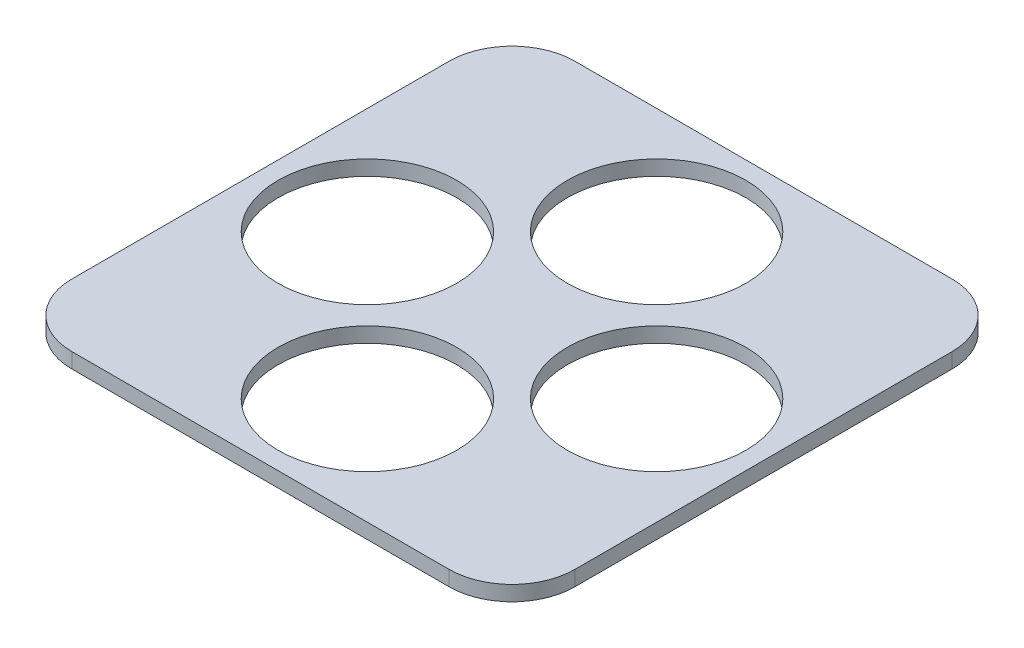
SolidWorks part; units mm, degrees
ref_plane "Plano frontal" through (0, 0, 0) normal (0, 0, 1) x (1, 0, 0)
ref_plane "Plano superior" through (0, 0, 0) normal (0, 1, 0) x (1, 0, 0)
ref_plane "Plano direito" through (0, 0, 0) normal (1, 0, 0) x (0, 0, -1)
sketch "Esboço1" plane through (0, 0, 0) normal (0, 1, 0) x (1, 0, 0)
  line L0 (0, 31.4255) -> (0, -26.6241) construction
  line L1 (-15, -20) -> (15, -20)
  line L2 (-20, -15) -> (-20, 15)
  line L3 (-15, 20) -> (15, 20)
  line L4 (20, -15) -> (20, 15)
  line L5 (-20, -20) -> (20, 20) construction
  line L6 (-20, 20) -> (20, -20) construction
  line L7 (-26.5891, 0) -> (32.2521, 0) construction
  circle A0 centre (0, 11.5) radius 7.1
  circle A1 centre (11.5, 0) radius 7.1
  circle A2 centre (0, -11.5) radius 7.1
  circle A3 centre (-11.5, 0) radius 7.1
  arc A4 (20, 15) -> (15, 20) centre (15, 15) ccw
  arc A5 (20, -15) -> (15, -20) centre (15, -15) cw
  arc A6 (-15, -20) -> (-20, -15) centre (-15, -15) cw
  arc A7 (-20, 15) -> (-15, 20) centre (-15, 15) cw
  point P0 (0, 0)
  dimension "D3" = 14.2
  dimension "D4" = 11.5
  dimension "D5" = 11.5
  dimension "D6" = 11.5
  dimension "D7" = 11.5
  dimension "D8" = 5
  dimension "D1" = 40
  dimension "D2" = 40
extrude "Ressalto-extrusão1" add sketch "Esboço1" along normal blind 1.2
